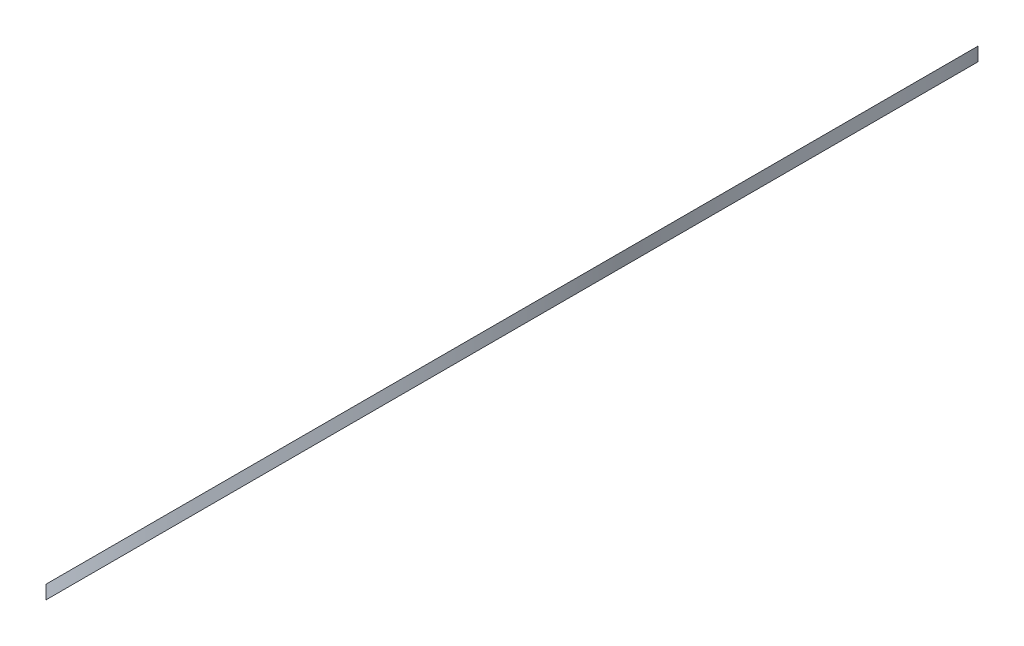
SolidWorks part; units mm, degrees
ref_plane "Front Plane" through (0, 0, 0) normal (0, 0, 1) x (1, 0, 0)
ref_plane "Top Plane" through (0, 0, 0) normal (0, 1, 0) x (1, 0, 0)
ref_plane "Right Plane" through (0, 0, 0) normal (1, 0, 0) x (0, 0, -1)
sketch "Sketch1" plane through (0, 0, 0) normal (0, 1, 0) x (1, 0, 0)
  circle A1 centre (0, 0) radius 35.5
  dimension "D2" = 71
sketch "Sketch3" plane through (0, 0, 0) normal (0, 0, 1) x (1, 0, 0)
  line L0 (-31.2551, 29.2277) -> (8.2156, 68.6984) construction
  line L1 (35.5, 0) -> (-35.5, 0) construction
  dimension "D1" = 45
ref_plane "Plane2" through (-30.2414, 30.2414, 0) normal (0.7071, -0.7071, 0) x (0.7071, 0.7071, 0)
sketch "Sketch4" plane through (-30.2414, 30.2414, 0) normal (0.7071, -0.7071, 0) x (0.7071, 0.7071, 0)
  line L1 (-116.2607, -93.0001) -> (116.2607, -93.0001)
  line L2 (-116.2607, -93.0001) -> (-116.2607, 93.0001)
  line L3 (-116.2607, 93.0001) -> (116.2607, 93.0001)
  line L4 (116.2607, -93.0001) -> (116.2607, 93.0001)
  line L5 (-116.2607, -93.0001) -> (116.2607, 93.0001) construction
  line L6 (-116.2607, 93.0001) -> (116.2607, -93.0001) construction
  point P0 (0, 0)
extrude "Boss-Extrude1" add sketch "Sketch4" along normal blind 1
extrude "Cut-Extrude2" cut sketch "Sketch1" along normal through all flip side to cut contours A1
sketch "Sketch5" plane through (0, 0, 0) normal (0, 1, 0) x (1, 0, 0)
  circle A2 centre (-67.416, 0) radius 62.5
  dimension "D1" = 125
extrude "Cut-Extrude3" cut sketch "Sketch5" against normal through all both and the other way through all
